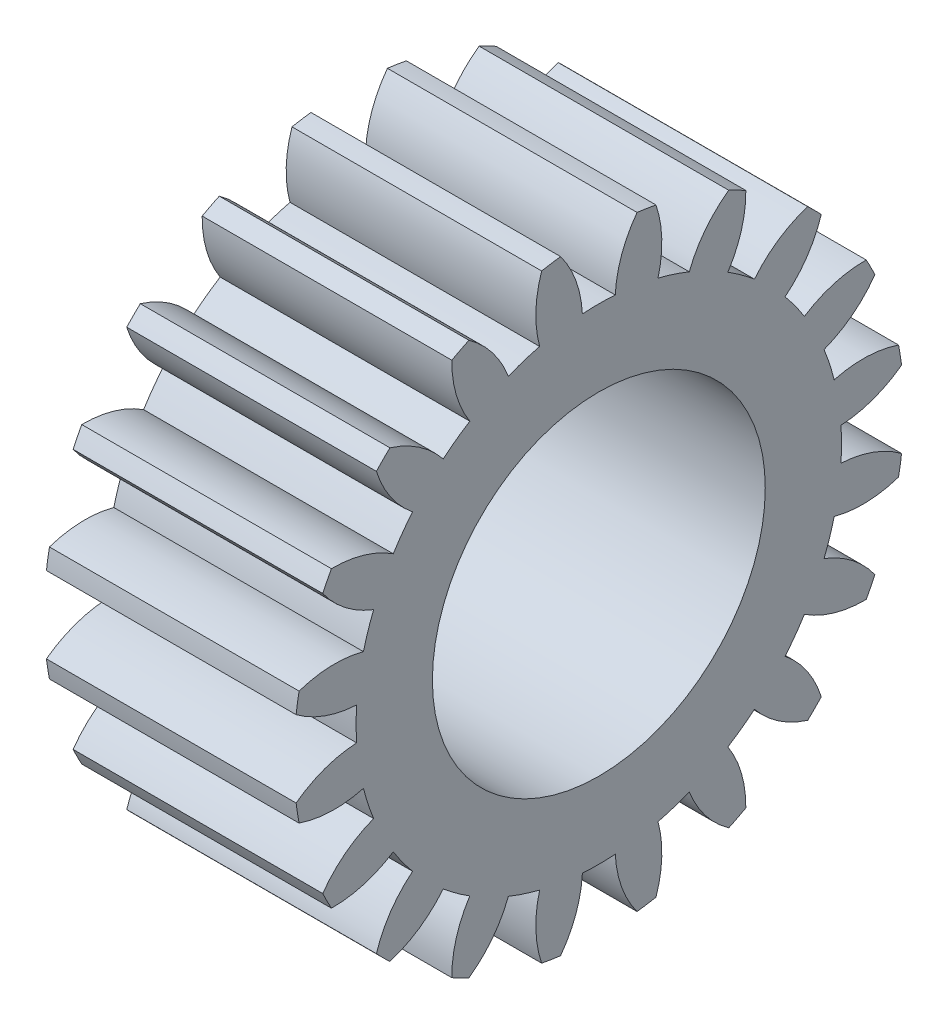
SolidWorks part; units mm, degrees
ref_plane "Plane1" through (0, 0, 0) normal (0, 0, 1) x (1, 0, 0)
ref_plane "Plane2" through (0, 0, 0) normal (0, 1, 0) x (1, 0, 0)
ref_plane "Plane3" through (0, 0, 0) normal (1, 0, 0) x (0, 0, -1)
sketch "HoldingSke" plane through (0, 0, 0) normal (0, 1, 0) x (1, 0, 0)
  line L0 (0, 0) -> (286.4183, -104.2477)
  line L1 (-15, 0) -> (100, 0) construction
  line L2 (0, 0) -> (-2.1039, 2.3779)
  line L3 (0, 0) -> (-11.863, 4.5341)
  line L4 (0, 0) -> (8.1152, 2.9537)
  line L5 (0, 0) -> (-47.5972, -17.7524)
  line L6 (0, 0) -> (-15.7917, -10.6547)
  line L7 (-2.1039, 2.3779) -> (8.8308, 51.9871)
  line L8 (-76.2, 54.61) -> (-47.9044, 54.61)
  line L9 (-67.7845, 28.3722) -> (-49.3413, 33.142)
  line L10 (-76.2, 71.12) -> (104.1128, 71.12)
  line L11 (0, 0) -> (-19.05, 0)
  line L12 (-76.2, 101.6) -> (-76.1147, 101.6)
  line L13 (24.9733, 27.94) -> (52.9518, 28.4284)
  line L14 (24.9733, 27.94) -> (24.9746, 27.94)
  line L15 (24.9733, 27.94) -> (100.4006, 29.5858)
  circle A0 centre (0, 0) radius 12.7
  circle A1 centre (0, 0) radius 18.5196
  circle A2 centre (0, 0) radius 38.1
  circle A3 centre (0, 0) radius 12.7
  dimension "MHD" = 37.0391
  dimension "Hub_dia" = 76.2
  dimension "Bore" = 25.4
  dimension "MBD" = 25.4
  dimension "Num_teeth" = 20
  dimension "Pitch" = 304.8
  dimension "Overall_len" = 50.8
  dimension "Show_teeth" = 20
  dimension "Thickness" = 19.05
  dimension "OAL" = 50.8001
  dimension "T_dim" = 28.2956
  dimension "Ap" = 14.5
  dimension "H" = 19.05
  dimension "Pitch_radius" = 180.3128
  dimension "Width" = 19.05
  dimension "Backlash" = 0.0853
  dimension "Addendum_fac" = 1
  dimension "Dedendum_fac" = 1.25
  dimension "Clearance_fac" = 0.25
  dimension "Dedendum_add" = 0.0013
sketch "BasProSke" plane through (0, 0, 0) normal (0, 1, 0) x (1, 0, 0)
  line L0 (-10, 0) -> (60, 0) construction
  line L1 (0, 0) -> (0, 23.2833)
  line L2 (0, 0) -> (19.05, 0)
  line L3 (19.05, 0) -> (19.05, 23.2833)
  line L4 (19.05, 23.2833) -> (0, 23.2833)
  dimension "Thickness" = 19.05
  dimension "Diameter" = 46.5667
revolve "Base-Revolve" add sketch "BasProSke" angle 360 about L0
sketch "TooCutSke" plane through (0, 0, 0) normal (1, 0, 0) x (0, 0, -1)
  line L1 (0, 0) -> (0, 107) construction
  line L2 (0, 0) -> (-1.81, 21.0891) construction
  line L3 (0, 0) -> (-6.6055, 41.7054) construction
  line L4 (-1.81, 21.0891) -> (-3.3027, 20.8527) construction
  arc A0 (1.255, 18.477) -> (-1.255, 18.477) centre (0, 0) ccw
  arc A1 (2.9355, 23.1231) -> (-2.9355, 23.1231) centre (0, 0) ccw
  circle A2 centre (0, 0) radius 21.1667 construction
  circle A3 centre (0, 0) radius 20.4925 construction
  arc A4 (-1.255, 18.477) -> (-2.9355, 23.1231) centre (-9.7107, 18.0456) ccw
  arc A5 (2.9355, 23.1231) -> (1.255, 18.477) centre (9.7107, 18.0456) ccw
  dimension "Root_dia" = 37.0391
  dimension "Overcut_dia" = 46.6175
  dimension "Pitch_dia" = 42.3333
  dimension "Base_dia" = 40.9849
  dimension "Flank_rad" = 8.4667
  dimension "Half_ang" = 9
  dimension "Half_CT" = 1.5114
extrude "ToothCut" cut sketch "TooCutSke" along normal through all
fillet "Breaks" [suppressed] radius 0.0423
fillet "RootFillets" [suppressed] radius 0.5304
pattern_circular "TeethCuts" count 20 every 18 about axis through (-10, 0, 0) along (1, 0, 0) of "ToothCut", "RootFillets", "Breaks"
sketch "HubNeaOneSke" plane through (0, 0, 0) normal (-1, 0, 0) x (0, 0, 1)
  circle A0 centre (0, 0) radius 18.5196
  dimension "Diameter" = 37.0391
extrude "HubNearOne" [suppressed] add sketch "HubNeaOneSke" along normal blind 31.7501
sketch "HubNeaBotSke" plane through (0, 0, 0) normal (-1, 0, 0) x (0, 0, 1)
  circle A0 centre (0, 0) radius 18.5196
  dimension "Diameter" = 37.0391
extrude "HubNearBoth" [suppressed] add sketch "HubNeaBotSke" along normal blind 15.875
ref_plane "FarPln" through (19.05, 0, 0) normal (1, 0, 0) x (0, 0, -1)
sketch "HubFarSke" plane through (19.05, 0, 0) normal (1, 0, 0) x (0, 0, -1)
  circle A0 centre (0, 0) radius 18.5196
  dimension "Diameter" = 37.0391
extrude "HubFar" [suppressed] add sketch "HubFarSke" along normal blind 15.875
sketch "BorSke" plane through (0, 0, 0) normal (1, 0, 0) x (0, 0, -1)
  circle A0 centre (0, 0) radius 12.7
  dimension "Diameter" = 25.4
extrude "Bore" cut sketch "BorSke" along normal mid plane 101.6001
sketch "KeySke" plane through (0, 0, 0) normal (1, 0, 0) x (0, 0, -1)
  line L0 (-3.175, 0) -> (-3.175, 15.5956)
  line L1 (-3.175, 15.5956) -> (3.175, 15.5956)
  line L2 (3.175, 15.5956) -> (3.175, 0)
  line L3 (0, 0) -> (0, 34) construction
  line L4 (-3.175, 0) -> (3.175, 0)
  dimension "Offset" = 15.5956
  dimension "Width" = 6.35
extrude "Keyway" [suppressed] cut sketch "KeySke" along normal mid plane 101.6001
pattern_circular "Keyway2" [suppressed] count 2 every 90 about axis through (-10, 0, 0) along (1, 0, 0)
equation "' \"Pitch@HoldingSke\" = 4"
equation "' \"Num_teeth@HoldingSke\" = 12"
equation "' \"Ap@HoldingSke\" =  20"
equation "' \"Ap@HoldingSke\" = 20"
equation "' \"Width@HoldingSke\" = 0.5"
equation "' \"Hub_dia@HoldingSke\"= 1"
equation "' \"Hub_dia@HoldingSke\" = 1"
equation "' \"Overall_len@HoldingSke\" = 1.0"
equation "' \"Bore@HoldingSke\" = 0.75"
equation "' \"T_dim@HoldingSke\" = 0.85"
equation "' \"Width@KeySke\" = 0.25"
equation "' \"Show_teeth@HoldingSke\" = 13"
equation "' \"Backlash@HoldingSke\" = 0.009"
equation "' \"Addendum_fac@HoldingSke\" = 1.0"
equation "' \"Dedendum_fac@HoldingSke\" = 1.25"
equation "' \"Dedendum_add@HoldingSke\" = 0.00005"
equation "' \"Clearance_fac@HoldingSke\" = 0.25"
equation "' \"Pitch@HoldingSke\" = 0.5"
equation "' \"Num_teeth@HoldingSke\" = 23"
equation "' \"Show_teeth@HoldingSke\" = 23"
equation "' \"Backlash@HoldingSke\" = 0.0375"
equation "\"Overcut_dia@TooCutSke\" = (\"Num_teeth@HoldingSke\" + 2 * \"Addendum_fac@HoldingSke\") / \"Pitch@HoldingSke\" + 0.002"
equation "\"Pitch_dia@TooCutSke\" = \"Num_teeth@HoldingSke\" / \"Pitch@HoldingSke\""
equation "\"Base_dia@TooCutSke\" = \"Num_teeth@HoldingSke\" / \"Pitch@HoldingSke\" * cos((\"Ap@HoldingSke\"  * 3.14159265 / 180))"
equation "\"Root_dia@TooCutSke\" = (\"Num_teeth@HoldingSke\" + 2) / \"Pitch@HoldingSke\" - 2 * (\"Addendum_fac@HoldingSke\" + \"Dedendum_fac@HoldingSke\") / \"Pitch@HoldingSke\" - \"Dedendum_add@HoldingSke\" * 2"
equation "\"Half_ang@TooCutSke\" = 180 / \"Num_teeth@HoldingSke\""
equation "\"Half_CT@TooCutSke\" = \"Num_teeth@HoldingSke\" / \"Pitch@HoldingSke\" * sin((3.14159265 / 2 / \"Num_teeth@HoldingSke\")) / 2 - 7 * \"Backlash@HoldingSke\" / 4"
equation "\"Flank_rad@TooCutSke\" = \"Num_teeth@HoldingSke\" / \"Pitch@HoldingSke\" / 5"
equation "\"Radius@RootFillets\" = \"Clearance_fac@HoldingSke\" / \"Pitch@HoldingSke\" + \"Dedendum_add@HoldingSke\""
equation "\"Break_rad@Breaks\" = 0.02 / \"Pitch@HoldingSke\""
equation "\"Thickness@HoldingSke\" = \"Width@HoldingSke\""
equation "\"OAL@HoldingSke\" = \"Thickness@HoldingSke\""
equation "\"MHD@HoldingSke\" = (\"Num_teeth@HoldingSke\" + 2) / \"Pitch@HoldingSke\" - 2 * (\"Addendum_fac@HoldingSke\" + \"Dedendum_fac@HoldingSke\")  / \"Pitch@HoldingSke\" - \"Dedendum_add@HoldingSke\" * 2"
equation "\"MBD@HoldingSke\" = (\"Num_teeth@HoldingSke\" + 2) / \"Pitch@HoldingSke\" - 2 * (\"Addendum_fac@HoldingSke\" + \"Dedendum_fac@HoldingSke\")  / \"Pitch@HoldingSke\" - \"Dedendum_add@HoldingSke\" * 2 - 0.002"
equation "\"MHD@HoldingSke\" = ((sgn( \"MHD@HoldingSke\" - \"Hub_dia@HoldingSke\" )-1)*( \"MHD@HoldingSke\" - \"Hub_dia@HoldingSke\" ))/-2+ \"Hub_dia@HoldingSke\""
equation "\"MBD@HoldingSke\" = ((sgn( \"MBD@HoldingSke\" - \"Bore@HoldingSke\" )-1)*( \"MBD@HoldingSke\" - \"Bore@HoldingSke\" ))/-2+ \"Bore@HoldingSke\""
equation "\"OAL@HoldingSke\" = ((sgn( \"OAL@HoldingSke\" - \"Overall_len@HoldingSke\" )+1)*( \"OAL@HoldingSke\" - \"Overall_len@HoldingSke\" ))/2 + \"Overall_len@HoldingSke\" + 0.000002"
equation "\"Num_teeth@TeethCuts\" = int( \"Show_teeth@HoldingSke\" ) + 1"
equation "\"Num_teeth@TeethCuts\" = ((sgn( \"Num_teeth@TeethCuts\" - \"Num_teeth@HoldingSke\" )-1)*( \"Num_teeth@TeethCuts\" - \"Num_teeth@HoldingSke\" ))/-2+ \"Num_teeth@HoldingSke\""
equation "\"Num_teeth@TeethCuts\" = ((sgn( \"Num_teeth@TeethCuts\" - 2.0)+1)*( \"Num_teeth@TeethCuts\" - 2.0))/2 +2.0"
equation "\"Angle@TeethCuts\" = 360.0 / \"Num_teeth@HoldingSke\""
equation "\"Diameter@BasProSke\" = (\"Num_teeth@HoldingSke\" + 2 * \"Addendum_fac@HoldingSke\") / \"Pitch@HoldingSke\""
equation "\"Thickness@BasProSke\"  = \"Thickness@HoldingSke\""
equation "' \"Fillet_rad@BasProSke\" =  \"Thickness@HoldingSke\" * 0.05"
equation "' \"Fillet_rad@BasProSke\" = \"Thickness@HoldingSke\" * 0.05"
equation "\"MHD@HoldingSke\" = ((sgn( \"MHD@HoldingSke\" - \"Root_dia@TooCutSke\" )-1)*( \"MHD@HoldingSke\" - \"Root_dia@TooCutSke\" ))/-2+ \"Root_dia@TooCutSke\""
equation "\"Diameter@HubNeaOneSke\" = \"MHD@HoldingSke\""
equation "\"Length@HubNearOne\" = \"OAL@HoldingSke\" - \"Thickness@BasProSke\""
equation "\"Diameter@HubNeaBotSke\" = \"MHD@HoldingSke\""
equation "\"Length@HubNearBoth\" = ( \"OAL@HoldingSke\" - \"Thickness@BasProSke\" ) / 2.0"
equation "\"Thickness@FarPln\" = \"Thickness@BasProSke\""
equation "\"Diameter@HubFarSke\" = \"MHD@HoldingSke\""
equation "\"Length@HubFar\" = ( \"OAL@HoldingSke\" - \"Thickness@BasProSke\" ) / 2.0"
equation "\"Diameter@BorSke\" = \"MBD@HoldingSke\""
equation "\"D1@Bore\" = \"OAL@HoldingSke\" * 2.0"
equation "\"D1@Keyway\" = \"OAL@HoldingSke\" * 2.0"
equation "\"Offset@KeySke\" = \"T_dim@HoldingSke\" - \"MBD@HoldingSke\" / 2.0"
